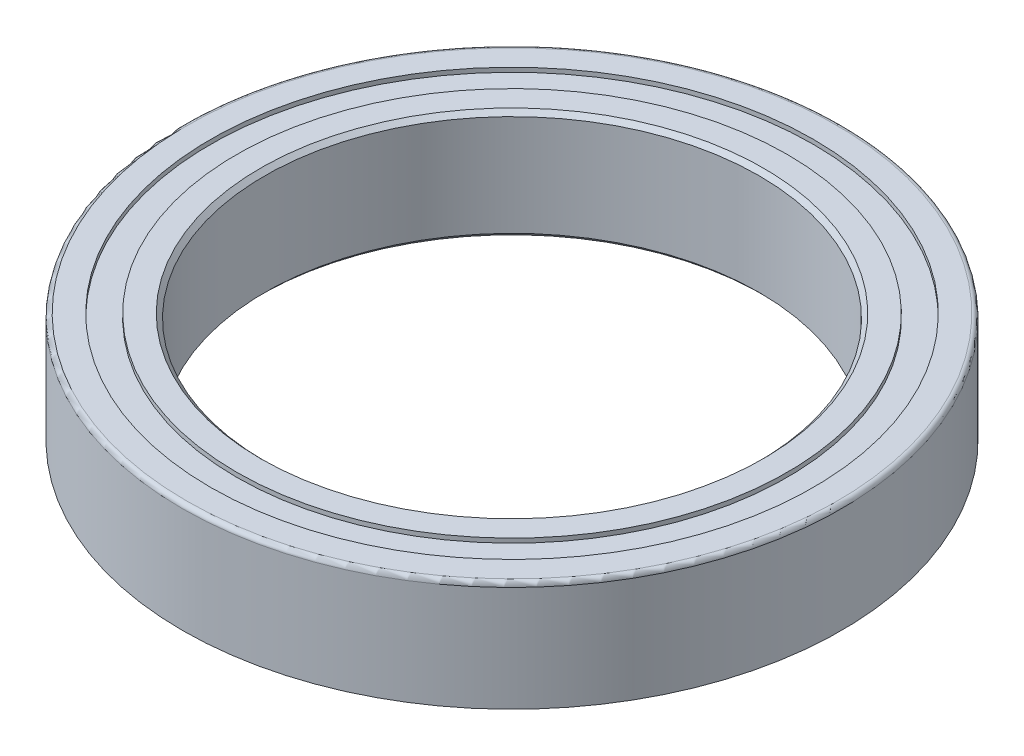
SolidWorks part; units mm, degrees
material "Chrome Stainless Steel"
ref_plane "Front Plane" through (0, 0, 0) normal (0, 0, 1) x (1, 0, 0)
ref_plane "Top Plane" through (0, 0, 0) normal (0, 1, 0) x (1, 0, 0)
ref_plane "Right Plane" through (0, 0, 0) normal (1, 0, 0) x (0, 0, -1)
sketch "Sketch1" plane through (0, 0, 0) normal (0, 1, 0) x (1, 0, 0)
  circle A0 centre (0, 0) radius 7.1438
  circle A1 centre (0, 0) radius 7.9566
  circle A2 centre (0, 0) radius 9.525
  circle A3 centre (0, 0) radius 8.7122
  dimension "D1" = 14.2875
  dimension "D3" = 19.05
  dimension "D2" = 0.8128
  dimension "D4" = 0.8128
extrude "Boss-Extrude1" add sketch "Sketch1" along normal mid plane 3.175 contours A2 A3 | A1 A0
fillet "Fillet1" radius 0.127 1 edges at (0, 1.5875, 9.525)
chamfer "Chamfer1" distance 0.127 2 edges at (0, -1.5875, 7.1438) (0, 1.5875, 7.1438)
sketch "Sketch2" plane through (0, 0, 0) normal (0, 1, 0) x (1, 0, 0)
  circle A0 centre (0, 0) radius 7.9566 construction
  circle A1 centre (0, 0) radius 8.7122 construction
  circle A2 centre (0, 0) radius 7.9566
  circle A3 centre (0, 0) radius 8.7122
extrude "Boss-Extrude2" add sketch "Sketch2" along normal mid plane 2.921
equation "\"D1@Boss-Extrude2\"= \"D1@Boss-Extrude1\" - .01in"
